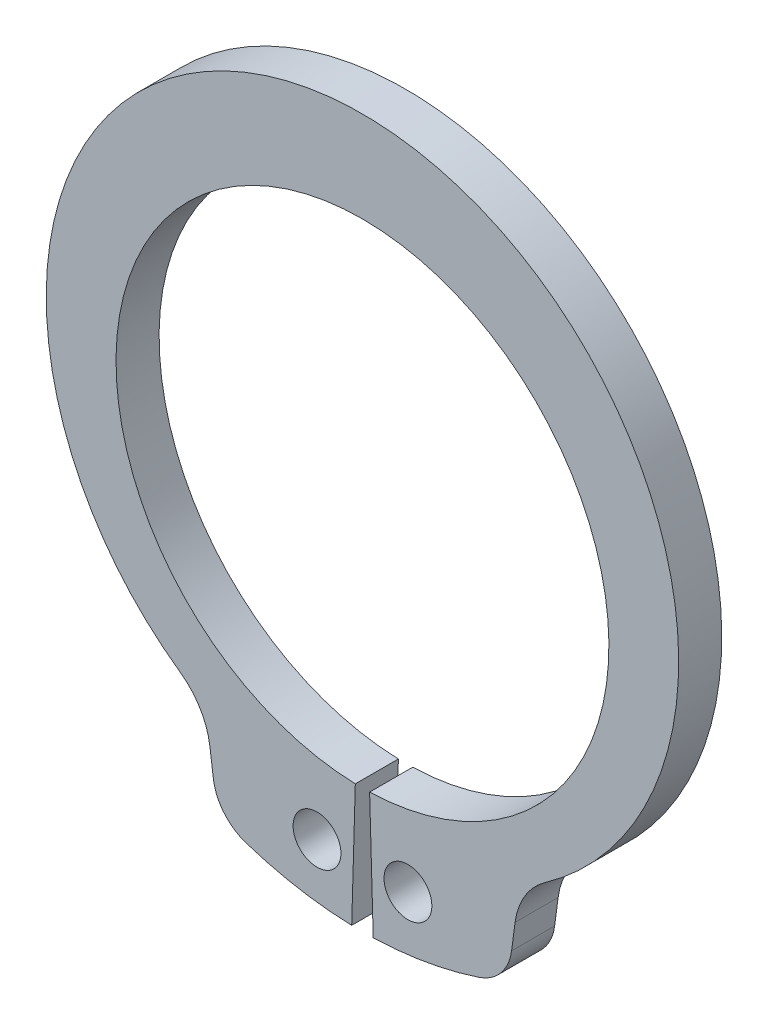
SolidWorks part; units mm, degrees
ref_plane "Plane1" through (0, 0, 0) normal (0, 0, 1) x (1, 0, 0)
ref_plane "Plane2" through (0, 0, 0) normal (0, 1, 0) x (1, 0, 0)
ref_plane "Plane3" through (0, 0, 0) normal (1, 0, 0) x (0, 0, -1)
extrude "Body" add sketch "BodySke" against normal blind 0.9
sketch "BodySke" plane through (0, 0, 0) normal (0, 0, 1) x (1, 0, 0)
  line L0 (-1.5431, 0) -> (1.5431, 0) construction
  line L1 (0, 0) -> (0, 7.05) construction
  line L2 (0.1495, -5.1478) -> (0.225, -7.7467)
  line L3 (-0.1495, -5.1478) -> (-0.225, -7.7467)
  line L4 (0, 0) -> (4.6748, -6.1813) construction
  line L5 (0, 0) -> (-4.6748, -6.1813) construction
  line L7 (3.1887, -5.9856) -> (3.116, -6.5375)
  line L8 (-3.1887, -5.9856) -> (-3.116, -6.5375)
  circle A0 centre (0, 0) radius 5.15 construction
  arc A1 (0.1495, -5.1478) -> (-0.1495, -5.1478) centre (0, 0) ccw
  arc A2 (3.77, -4.9849) -> (-3.77, -4.9849) centre (0, 0.442) ccw construction
  arc A3 (0.225, -7.7467) -> (2.4393, -7.3561) centre (0, 0) ccw
  arc A4 (3.8105, -4.9566) -> (3.1887, -5.9856) centre (4.6748, -6.1813) ccw
  arc A5 (-3.1887, -5.9856) -> (-3.8105, -4.9566) centre (-4.6748, -6.1813) ccw
  arc A6 (-2.4393, -7.3561) -> (-0.225, -7.7467) centre (0, 0) ccw
  arc A7 (3.8105, -4.9566) -> (-3.8105, -4.9566) centre (0, 0.442) ccw
  arc A8 (-3.214, -5.7932) -> (3.214, -5.7932) centre (0, 0) ccw construction
  circle A9 centre (0.95, -6.5565) radius 0.5
  circle A10 centre (-0.95, -6.5565) radius 0.5
  arc A11 (3.116, -6.5375) -> (2.4393, -7.3561) centre (2.1246, -6.4069) cw
  arc A12 (-3.116, -6.5375) -> (-2.4393, -7.3561) centre (-2.1246, -6.4069) ccw
  point P28 (3.038, -7.1297)
  point P31 (-3.038, -7.1297)
  dimension "GrooveDia" = 10.3
  dimension "D3" = 1
  dimension "LugRad" = 7.75
  dimension "HoleOffsetRad" = 6.625
  dimension "HoleDia" = 1
  dimension "D2" = 15
  dimension "LargeRad" = 7.05
  dimension "SmallRad" = 6.25
  dimension "Gap" = 0.45
  dimension "SmallAngle" = 74.2
  dimension "HoleSpacing" = 1.9
sketch "Clipboard" plane through (0, 0, 0) normal (0, 0, 1) x (1, 0, 0)
  line L0 (0, 0) -> (1.9, 0)
  line L1 (0, 0) -> (0, 1.1)
  line L2 (0, 0) -> (0, -2.6)
  circle A0 centre (0, 0) radius 0.5
  circle A1 centre (0, 0) radius 5.5
  dimension "HoleDia" = 1
  dimension "ShaftDia" = 11
  dimension "LargeSection" = 1.9
  dimension "SmallSection" = 1.1
  dimension "LugSection" = 2.6
sketch "NotSke" plane through (0, 0, 0) normal (0, 0, 1) x (1, 0, 0)
  line L0 (0.95, -6.0565) -> (0.95, -7.0565)
  line L1 (0.95, -7.0565) -> (-0.95, -7.0565)
  line L2 (-0.95, -7.0565) -> (-0.95, -6.0565)
  line L3 (-0.95, -6.0565) -> (0.95, -6.0565)
  circle A0 centre (0.95, -6.5565) radius 0.5 construction
  circle A1 centre (-0.95, -6.5565) radius 0.5 construction
extrude "Notch" [suppressed] cut sketch "NotSke" against normal through all
equation "' \"ShaftDia@Clipboard\" = 10"
equation "' \"Thickness@Body\" = 0.9"
equation "' \"GrooveDia@BodySke\" = 9.4"
equation "' \"LugSection@Clipboard\" = 2.6"
equation "' \"LargeSection@Clipboard\" = 1.7"
equation "' \"SmallSection@Clipboard\" = 1.0"
equation "' \"HoleDia@Clipboard\" = 1.0"
equation "' \"ShaftDia@Clipboard\" = 30"
equation "' \"Thickness@Body\" = 2.4"
equation "' \"GrooveDia@BodySke\" = 28.2"
equation "' \"LugSection@Clipboard\" = 5.6"
equation "' \"LargeSection@Clipboard\" = 4.5"
equation "' \"SmallSection@Clipboard\" = 2.5"
equation "' \"HoleDia@Clipboard\" = 2.3"
equation "\"Gap@BodySke\" =  \"Thickness@Body\" / 2"
equation "\"LargeRad@BodySke\" =  \"GrooveDia@BodySke\" / 2 +  \"LargeSection@Clipboard\""
equation "\"SmallRad@BodySke\" =  \"GrooveDia@BodySke\" / 2 +  \"SmallSection@Clipboard\""
equation "\"LugRad@BodySke\" = \"GrooveDia@BodySke\" / 2 + \"LugSection@Clipboard\""
equation "\"HoleOffsetRad@BodySke\" = (  \"ShaftDia@Clipboard\" / 2 + \"LugRad@BodySke\" ) / 2"
equation "\"HoleSpacing@BodySke\" = \"Gap@BodySke\"  * 2 +  \"HoleDia@Clipboard\""
equation "\"HoleDia@BodySke\" =  \"HoleDia@Clipboard\""
equation "\"SmallAngle@BodySke\" = atn(\"HoleSpacing@BodySke\" / 2 / sqr(\"HoleOffsetRad@BodySke\"  * \"HoleOffsetRad@BodySke\" - (\"HoleSpacing@BodySke\" / 2) * (\"HoleSpacing@BodySke\" / 2) ))  * 9 * ( 180 / 3.141593)"
